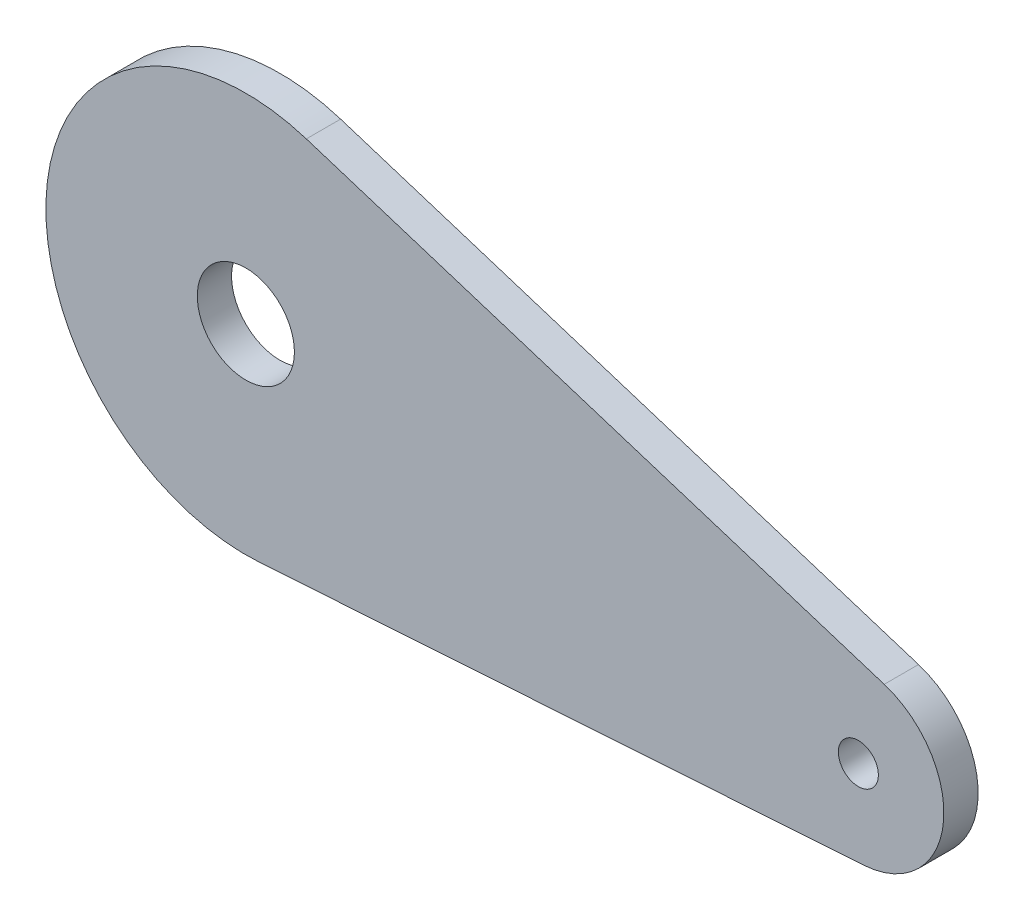
SolidWorks part; units mm, degrees
ref_plane "Front Plane" through (0, 0, 0) normal (0, 0, 1) x (1, 0, 0)
ref_plane "Top Plane" through (0, 0, 0) normal (0, 1, 0) x (1, 0, 0)
ref_plane "Right Plane" through (0, 0, 0) normal (1, 0, 0) x (0, 0, -1)
sketch "Sketch1" plane through (0, 0, 0) normal (0, 0, 1) x (1, 0, 0)
  line L0 (-20.22, 57.58) -> (33.3867, 51.0741) construction
  line L1 (-20.22, 57.58) -> (33.3867, 51.0741) construction
  line L2 (-14.9261, 74.2601) -> (35.6508, 58.2082)
  line L3 (-19.0698, 40.1178) -> (33.8786, 43.6056)
  circle A0 centre (-20.22, 57.58) radius 17.5 construction
  circle A1 centre (-20.22, 57.58) radius 17.5 construction
  circle A2 centre (33.3867, 51.0741) radius 7.4847 construction
  arc A3 (-14.9261, 74.2601) -> (-19.0698, 40.1178) centre (-20.22, 57.58) ccw
  arc A4 (35.6508, 58.2082) -> (33.8786, 43.6056) centre (33.3867, 51.0741) cw
  circle A5 centre (33.3867, 51.0741) radius 1.75
  circle A6 centre (-20.22, 57.58) radius 4.25
  dimension "D1" = 8.5
  dimension "D2" = 3.5
extrude "Boss-Extrude1" add sketch "Sketch1" against normal blind 3
